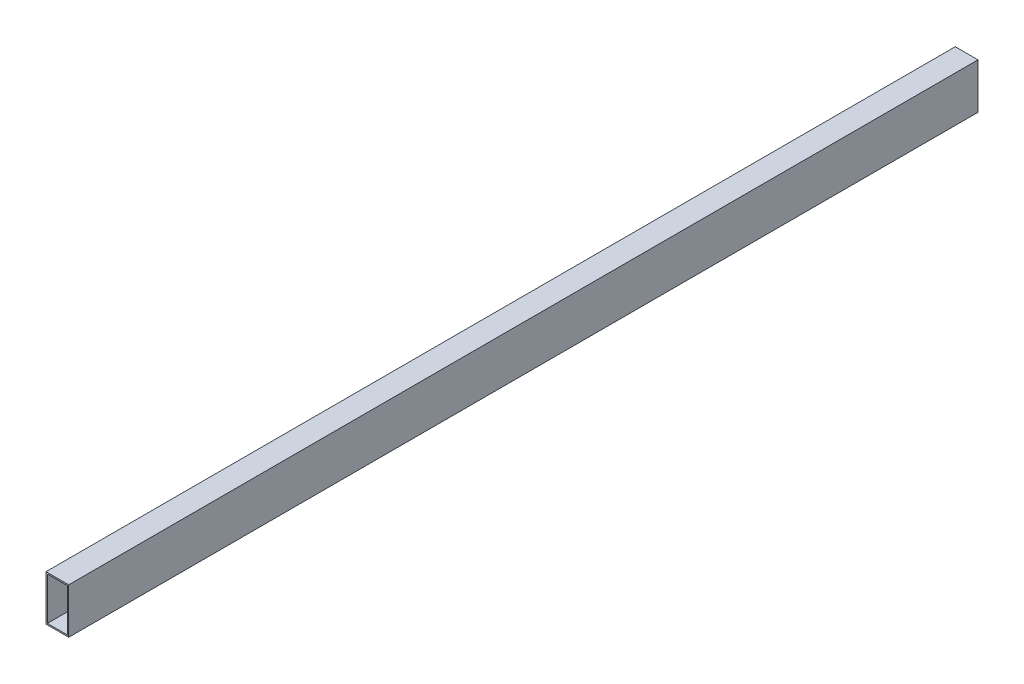
SolidWorks part; units mm, degrees
ref_plane "Front Plane" through (0, 0, 0) normal (0, 0, 1) x (1, 0, 0)
ref_plane "Top Plane" through (0, 0, 0) normal (0, 1, 0) x (1, 0, 0)
ref_plane "Right Plane" through (0, 0, 0) normal (1, 0, 0) x (0, 0, -1)
sketch "Sketch1" plane through (0, 0, 0) normal (0, 0, 1) x (1, 0, 0)
  line L1 (0, 0) -> (25.4, 0)
  line L2 (0, 0) -> (0, 50.8)
  line L3 (0, 50.8) -> (25.4, 50.8)
  line L4 (25.4, 0) -> (25.4, 50.8)
  dimension "D1" = 25.4
  dimension "D2" = 50.8
extrude "Extrude-Thin1" add sketch "Sketch1" along normal blind 1016 thin thin type one direction reverse wall 1.524
